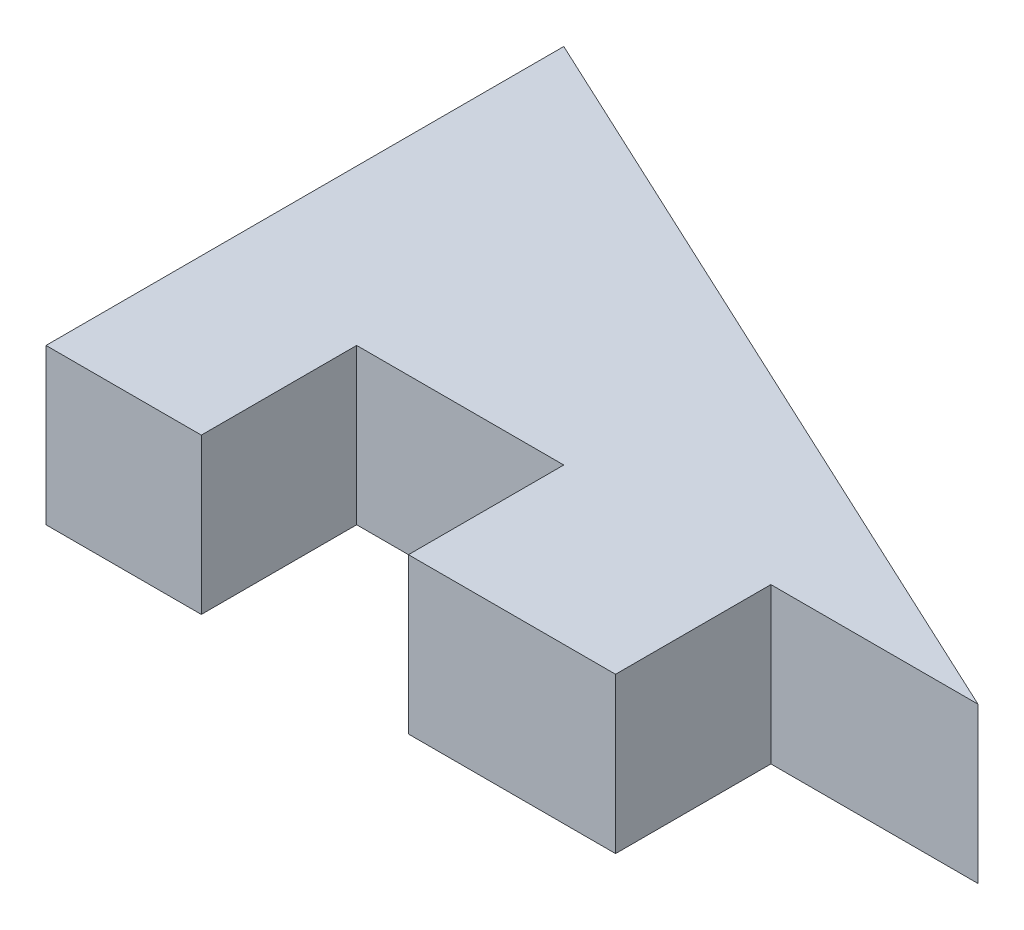
SolidWorks part; units mm, degrees
ref_plane "Front Plane" through (0, 0, 0) normal (0, 0, 1) x (1, 0, 0)
ref_plane "Top Plane" through (0, 0, 0) normal (0, 1, 0) x (1, 0, 0)
ref_plane "Right Plane" through (0, 0, 0) normal (1, 0, 0) x (0, 0, -1)
sketch "Sketch1" plane through (0, 0, 0) normal (0, 1, 0) x (1, 0, 0)
  line L2 (-4, 0) -> (-4, 3)
  line L4 (-8, 3) -> (-8, 0)
  line L6 (-12, 0) -> (-12, 3)
  line L7 (-12, 3) -> (-8, 3)
  line L8 (-15, 3) -> (-15, 10)
  line L9 (-15, 10) -> (0, 3)
  line L10 (-8, 0) -> (-4, 0)
  line L11 (-12, 0) -> (-15, 0)
  line L12 (-15, 0) -> (-15, 3)
  line L13 (-4, 3) -> (0, 3)
  dimension "D1" = 4
  dimension "D2" = 4
  dimension "D3" = 4
  dimension "D4" = 4
  dimension "D5" = 3
  dimension "D6" = 3
  dimension "D7" = 7
  dimension "D8" = 4
  dimension "D9" = 3
extrude "Boss-Extrude1" add sketch "Sketch1" along normal blind 3
